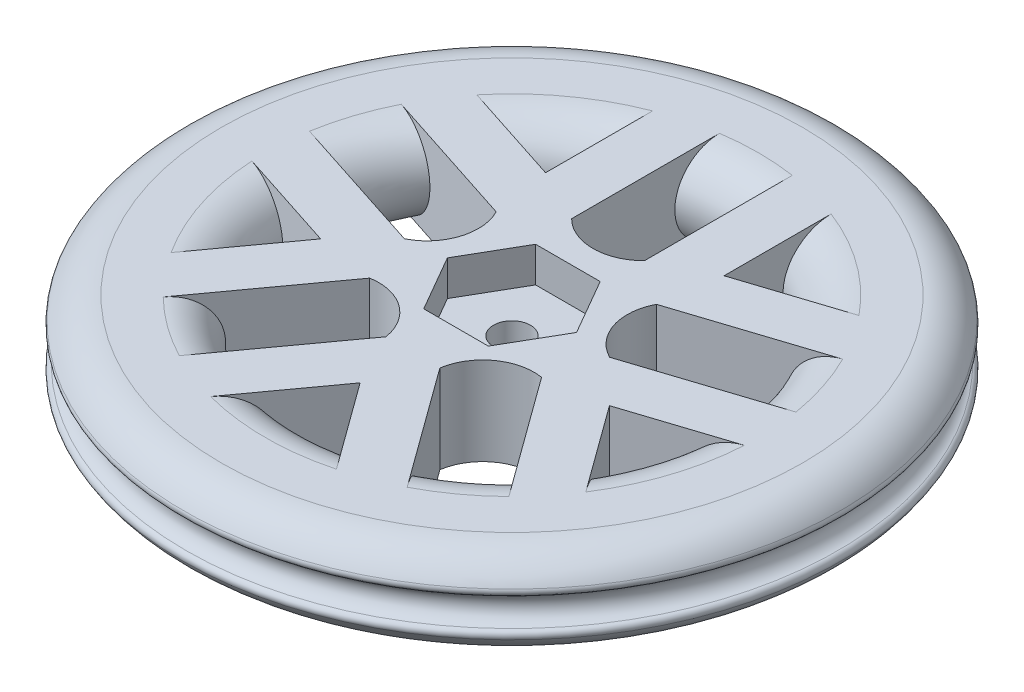
SolidWorks part; units mm, degrees
ref_plane "前视基准面" through (0, 0, 0) normal (0, 0, 1) x (1, 0, 0)
ref_plane "上视基准面" through (0, 0, 0) normal (0, 1, 0) x (1, 0, 0)
ref_plane "右视基准面" through (0, 0, 0) normal (1, 0, 0) x (0, 0, -1)
other "Configuration Table"
sketch "草图1" plane through (0, 0, 0) normal (1, 0, 0) x (0, 0, -1)
  line L0 (0, 0) -> (0, 6.1282) construction
  line L1 (0, 0) -> (9, 0)
  line L2 (0, 0) -> (0, -10)
  line L3 (0, -10) -> (9, -10)
  line L4 (9, 0) -> (9, -10)
  dimension "D1" = 9
  dimension "D2" = 10
revolve "旋转1" add sketch "草图1" angle 360 about L0
sketch "草图2" plane through (0, 0, 0) normal (0, 1, 0) x (1, 0, 0)
  line L1 (7.2733, -0.1394) -> (3.7574, 6.2291)
  line L2 (3.7574, 6.2291) -> (-3.5159, 6.3685)
  line L3 (-3.5159, 6.3685) -> (-7.2733, 0.1394)
  line L4 (-7.2733, 0.1394) -> (-3.7574, -6.2291)
  line L5 (-3.7574, -6.2291) -> (3.5159, -6.3685)
  line L6 (3.5159, -6.3685) -> (7.2733, -0.1394)
  circle A0 centre (0, 0) radius 6.3 construction
  dimension "D1" = 12.6
extrude "切除-拉伸1" cut sketch "草图2" against normal blind 4
sketch "草图4" plane through (0, 0, 0) normal (0, 0, 1) x (1, 0, 0)
  line L0 (0, 0) -> (0, 13.7912) construction
  line L1 (28, 0) -> (33, 0)
  line L4 (33, -10) -> (28, -10)
  arc A0 (28, 0) -> (28, -10) centre (28, -5) ccw
  arc A2 (33, -10) -> (33, 0) centre (33, -5) ccw
  dimension "D1" = 10
  dimension "D4" = 10
  dimension "D2" = 28
  dimension "D3" = 5
  dimension "D5" = 5
revolve "旋转2" add sketch "草图4" angle 360 about L0
sketch "草图5" plane through (0, 0, 0) normal (0, 1, 0) x (1, 0, 0)
  line L0 (0, 30) -> (0, 0) construction
  line L1 (0, 30) -> (-28.5317, 9.2705) construction
  line L2 (-28.5317, 9.2705) -> (-17.6336, -24.2705) construction
  line L3 (-17.6336, -24.2705) -> (17.6336, -24.2705) construction
  line L4 (17.6336, -24.2705) -> (28.5317, 9.2705) construction
  line L5 (28.5317, 9.2705) -> (0, 30) construction
  line L6 (0, 0) -> (-28.5317, 9.2705) construction
  line L7 (-17.6336, -24.2705) -> (0, 0) construction
  line L8 (0, 0) -> (17.6336, -24.2705) construction
  line L9 (28.5317, 9.2705) -> (0, 0) construction
  line L10 (0, 0) -> (-14.2658, 19.6353) construction
  line L11 (0, 0) -> (14.2658, 19.6353) construction
  line L12 (0, 0) -> (23.0826, -7.5) construction
  line L13 (0, 0) -> (23.0826, -7.5) construction
  line L14 (0, 0) -> (0, -24.2705) construction
  line L15 (0, 0) -> (-23.0826, -7.5) construction
  line L16 (-7.1329, 9.8176) -> (-7.1329, 27.0762) construction
  line L17 (7.1329, 9.8176) -> (7.1329, 27.0762) construction
  line L18 (4.1329, 10.9069) -> (4.1329, 27.0762)
  line L19 (-4.1329, 10.9069) -> (-4.1329, 27.0762)
  line L20 (10.1329, 8.9205) -> (10.1329, 27.0762)
  line L21 (-10.1329, 8.9205) -> (-10.1329, 27.0762)
  line L22 (4.1329, 27.0762) -> (4.1329, 29.0762)
  line L23 (4.1329, 29.0762) -> (10.1329, 29.0762)
  line L24 (10.1329, 29.0762) -> (10.1329, 27.0762)
  line L25 (-10.1329, 27.0762) -> (-10.1329, 29.0762)
  line L26 (-10.1329, 29.0762) -> (-4.1329, 29.0762)
  line L27 (-4.1329, 29.0762) -> (-4.1329, 27.0762)
  line L28 (11.6152, -6.8804) -> (28.8823, -1.27)
  line L29 (11.6502, -0.5602) -> (27.0282, 4.4364)
  line L30 (27.0282, 4.4364) -> (28.9303, 5.0544)
  line L31 (28.9303, 5.0544) -> (30.7844, -0.6519)
  line L32 (30.7844, -0.6519) -> (28.8823, -1.27)
  line L33 (26.376, 12.9157) -> (24.4739, 12.2977)
  line L34 (24.5219, 18.622) -> (26.376, 12.9157)
  line L35 (22.6198, 18.004) -> (24.5219, 18.622)
  line L36 (9.0959, 7.301) -> (24.4739, 12.2977)
  line L37 (5.3527, 12.3936) -> (22.6198, 18.004)
  line L38 (-2.9544, -13.1728) -> (7.7173, -27.8611)
  line L39 (3.0673, -11.2531) -> (12.5714, -24.3344)
  line L40 (12.5714, -24.3344) -> (13.747, -25.9524)
  line L41 (13.747, -25.9524) -> (8.8929, -29.4791)
  line L42 (8.8929, -29.4791) -> (7.7173, -27.8611)
  line L43 (20.4342, -21.0939) -> (19.2586, -19.4758)
  line L44 (25.2883, -17.5672) -> (20.4342, -21.0939)
  line L45 (24.1127, -15.9491) -> (25.2883, -17.5672)
  line L46 (9.7545, -6.3946) -> (19.2586, -19.4758)
  line L47 (13.4411, -1.2609) -> (24.1127, -15.9491)
  line L48 (-13.4411, -1.2609) -> (-24.1127, -15.9491)
  line L49 (-9.7545, -6.3946) -> (-19.2586, -19.4758)
  line L50 (-19.2586, -19.4758) -> (-20.4342, -21.0939)
  line L51 (-20.4342, -21.0939) -> (-25.2883, -17.5672)
  line L52 (-25.2883, -17.5672) -> (-24.1127, -15.9491)
  line L53 (-13.747, -25.9524) -> (-12.5714, -24.3344)
  line L54 (-8.8929, -29.4791) -> (-13.747, -25.9524)
  line L55 (-7.7173, -27.8611) -> (-8.8929, -29.4791)
  line L56 (-3.0673, -11.2531) -> (-12.5714, -24.3344)
  line L57 (2.9544, -13.1728) -> (-7.7173, -27.8611)
  line L58 (-5.3527, 12.3936) -> (-22.6198, 18.004)
  line L59 (-9.0959, 7.301) -> (-24.4739, 12.2977)
  line L60 (-24.4739, 12.2977) -> (-26.376, 12.9157)
  line L61 (-26.376, 12.9157) -> (-24.5219, 18.622)
  line L62 (-24.5219, 18.622) -> (-22.6198, 18.004)
  line L63 (-28.9303, 5.0544) -> (-27.0282, 4.4364)
  line L64 (-30.7844, -0.6519) -> (-28.9303, 5.0544)
  line L65 (-28.8823, -1.27) -> (-30.7844, -0.6519)
  line L66 (-11.6502, -0.5602) -> (-27.0282, 4.4364)
  line L67 (-11.6152, -6.8804) -> (-28.8823, -1.27)
  circle A0 centre (0, 0) radius 24.2705 construction
  arc A1 (-7.1329, 9.8176) -> (7.1329, 9.8176) centre (0, 15) ccw construction
  circle A2 centre (0, 0) radius 28 construction
  arc A3 (-4.1329, 10.9069) -> (4.1329, 10.9069) centre (0, 15) ccw
  arc A4 (-10.1329, 8.9205) -> (10.1329, 8.9205) centre (0, 15) ccw
  arc A5 (9.0959, 7.301) -> (11.6502, -0.5602) centre (14.2658, 4.6353) ccw
  arc A6 (5.3527, 12.3936) -> (11.6152, -6.8804) centre (14.2658, 4.6353) ccw
  arc A7 (9.7545, -6.3946) -> (3.0673, -11.2531) centre (8.8168, -12.1353) ccw
  arc A8 (13.4411, -1.2609) -> (-2.9544, -13.1728) centre (8.8168, -12.1353) ccw
  arc A9 (-3.0673, -11.2531) -> (-9.7545, -6.3946) centre (-8.8168, -12.1353) ccw
  arc A10 (2.9544, -13.1728) -> (-13.4411, -1.2609) centre (-8.8168, -12.1353) ccw
  arc A11 (-11.6502, -0.5602) -> (-9.0959, 7.301) centre (-14.2658, 4.6353) ccw
  arc A12 (-11.6152, -6.8804) -> (-5.3527, 12.3936) centre (-14.2658, 4.6353) ccw
  point P16 (0, 0)
  point P94 (0, 0)
  circle M15 centre (0, 0) radius 28
  dimension "D2" = 17.6336
  dimension "D5" = 2
  dimension "D6" = 2
  dimension "D7" = 5
  dimension "D3" = 3
  dimension "D4" = 3
  dimension "D1" = 5
extrude "凸台-拉伸1" add sketch "草图5" against normal blind 10 contours A12 A4 A6 L37 L20 L22 L18 A3 L19 L27 L21 L58 M15 | L37 A6 A4 L20 | A8 L47 L28 L30 L29 A5 L36 L33 L37 L20 A4 A6 M15 | L47 A8 A6 L28 | L32 L31 L30 L28 M15 | L37 L33 L34 L35 M15 | L24 L23 L22 L20 M15 | L27 L26 L25 L21 M15 | A4 A12 L58 L21 | A10 A12 A4 L21 L58 L60 L59 A11 L66 L63 L67 L48 M15 | L62 L61 L60 L58 M15 | L67 L63 L64 L65 M15 | L67 A12 A10 L48 | A12 L67 L48 L50 L49 A9 L56 L53 L57 L38 A8 A10 M15 | L52 L51 L50 L48 M15 | L57 L53 L54 L55 M15 | L57 A10 A8 L38 | A10 L57 L38 L40 L39 A7 L46 L43 L47 L28 A6 A8 M15 | L42 L41 L40 L38 M15 | L47 L43 L44 L45 M15 | A12 A10 A8 A6 A4
sketch "草图6" plane through (0, -10, 0) normal (0, -1, 0) x (1, 0, 0)
  line L2 (-22.6517, 17.0006) -> (-12.291, 2.7403)
  line L3 (1.192, 12.5362) -> (-9.1687, 26.7965)
  line L4 (-22.0484, 18.2117) -> (-11.5413, 3.75)
  line L5 (0, 12.1353) -> (-10.5071, 26.597)
  line L6 (-21.8811, 17.9815) -> (-11.5413, 3.75) construction
  line L7 (0, 12.1353) -> (-10.5071, 26.597) construction
  line L8 (-21.0776, 18.9171) -> (-10.809, 4.7836)
  line L9 (-1.2093, 11.7582) -> (-11.4779, 25.8916)
  line L10 (12.291, 2.7403) -> (22.6517, 17.0006)
  line L11 (-22.0484, 18.2117) -> (-11.5413, 3.75) construction
  line L12 (-23.0192, 17.5064) -> (-12.291, 2.7403) construction
  line L13 (1.192, 12.5362) -> (-9.5362, 27.3023) construction
  line L14 (10.809, 4.7836) -> (21.0776, 18.9171)
  line L15 (11.4779, 25.8916) -> (1.2093, 11.7582)
  line L16 (9.1687, 26.7965) -> (-1.192, 12.5362)
  line L17 (6.4043, -10.8426) -> (23.1683, -16.2896)
  line L18 (7.8897, -8.8018) -> (24.5045, -14.2002)
  line L19 (28.1713, -2.9152) -> (11.5564, 2.4833)
  line L20 (28.3183, -0.4394) -> (11.5543, 5.0075)
  line L21 (-8.3329, -9.4414) -> (-8.3329, -27.0681)
  line L22 (-5.9329, -10.2234) -> (-5.9329, -27.6933)
  line L23 (5.9329, -27.6933) -> (5.9329, -10.2234)
  line L24 (8.3329, -27.0681) -> (8.3329, -9.4414)
  line L25 (-11.5543, 5.0075) -> (-28.3183, -0.4394)
  line L26 (-11.5564, 2.4833) -> (-28.1713, -2.9152)
  line L27 (-24.5045, -14.2002) -> (-7.8897, -8.8018)
  line L28 (-23.1683, -16.2896) -> (-6.4043, -10.8426)
  arc A1 (-12.291, 2.7403) -> (1.192, 12.5362) centre (-8.8168, 12.1353) ccw
  arc A2 (-11.5413, 3.75) -> (0, 12.1353) centre (-8.8168, 12.1353) ccw
  arc A3 (-11.5413, 3.75) -> (0, 12.1353) centre (-8.8168, 12.1353) ccw construction
  arc A4 (-10.809, 4.7836) -> (-1.2093, 11.7582) centre (-8.8168, 12.1353) ccw
  arc A5 (-9.1687, 26.7965) -> (-11.4779, 25.8916) centre (0, 0) ccw
  arc A6 (-21.0776, 18.9171) -> (-22.6517, 17.0006) centre (0, 0) ccw
  arc A7 (-1.192, 12.5362) -> (12.291, 2.7403) centre (8.8168, 12.1353) ccw
  arc A8 (22.6517, 17.0006) -> (21.0776, 18.9171) centre (0, 0) ccw
  arc A9 (1.2093, 11.7582) -> (10.809, 4.7836) centre (8.8168, 12.1353) ccw
  arc A10 (11.4779, 25.8916) -> (9.1687, 26.7965) centre (0, 0) ccw
  arc A11 (11.5543, 5.0075) -> (6.4043, -10.8426) centre (14.2658, -4.6353) ccw
  arc A12 (23.1683, -16.2896) -> (24.5045, -14.2002) centre (0, 0) ccw
  arc A13 (11.5564, 2.4833) -> (7.8897, -8.8018) centre (14.2658, -4.6353) ccw
  arc A14 (28.1713, -2.9152) -> (28.3183, -0.4394) centre (0, 0) ccw
  arc A15 (8.3329, -9.4414) -> (-8.3329, -9.4414) centre (0, -15) ccw
  arc A16 (-8.3329, -27.0681) -> (-5.9329, -27.6933) centre (0, 0) ccw
  arc A17 (5.9329, -10.2234) -> (-5.9329, -10.2234) centre (0, -15) ccw
  arc A18 (5.9329, -27.6933) -> (8.3329, -27.0681) centre (0, 0) ccw
  arc A19 (-6.4043, -10.8426) -> (-11.5543, 5.0075) centre (-14.2658, -4.6353) ccw
  arc A20 (-28.3183, -0.4394) -> (-28.1713, -2.9152) centre (0, 0) ccw
  arc A21 (-7.8897, -8.8018) -> (-11.5564, 2.4833) centre (-14.2658, -4.6353) ccw
  arc A22 (-24.5045, -14.2002) -> (-23.1683, -16.2896) centre (0, 0) ccw
  point P63 (0, 0)
  dimension "D1" = 3
  dimension "D2" = 1.2
  dimension "D3" = 1.2
  dimension "D4" = 5
extrude "切除-拉伸2" cut sketch "草图6" against normal blind 2.5 contours A19 A1 A7 L16 L3 A5 L9 A4 L8 A6 L2 L25 | A11 L20 L10 A8 L14 A9 L15 A10 L16 L3 A1 A7 | A15 L24 L17 A12 L18 A13 L19 A14 L20 L10 A7 A11 | A19 L28 L21 A16 L22 A17 L23 A18 L24 L17 A11 A15 | L27 A22 L28 L21 A15 A19 A1 L2 L25 A20 L26 A21 | L28 A19 A15 L21 | L24 A15 A11 L17 | L20 A11 A7 L10 | L16 A7 A1 L3 | A1 A19 L25 L2 | A19 A15 A11 A7 A1
sketch "草图7" plane through (0, 0, 0) normal (0, 1, 0) x (1, 0, 0)
  line L1 (7.3323, 0) -> (3.6662, 6.35)
  line L2 (3.6662, 6.35) -> (-3.6662, 6.35)
  line L3 (-3.6662, 6.35) -> (-7.3323, 0)
  line L4 (-7.3323, 0) -> (-3.6662, -6.35)
  line L5 (-3.6662, -6.35) -> (3.6662, -6.35)
  line L6 (3.6662, -6.35) -> (7.3323, 0)
  circle A0 centre (0, 0) radius 6.35 construction
  dimension "D1" = 12.7
extrude "切除-拉伸3" cut sketch "草图7" against normal blind 4
sketch "草图8" plane through (0, -4, 0) normal (0, 1, 0) x (1, 0, 0)
  circle A0 centre (0, 0) radius 2.1
  dimension "D1" = 4.2
extrude "切除-拉伸4" cut sketch "草图8" against normal through all
sketch "草图9" plane through (0, 0, 0) normal (0, 0, 1) x (1, 0, 0)
  line L0 (0, 0) -> (0, 35.058) construction
  line L1 (33, 0) -> (-33, 0) construction
  circle A0 centre (37.5, -5) radius 1.7
  dimension "D1" = 3.4
  dimension "D2" = 37.5
  dimension "D3" = 5
revolve "切除-旋转1" cut sketch "草图9" angle 360 about L0
fillet "圆角1" radius 0.6 2 edges at (0, -6.6874, 37.7067) (0, -3.3126, -37.7067)
